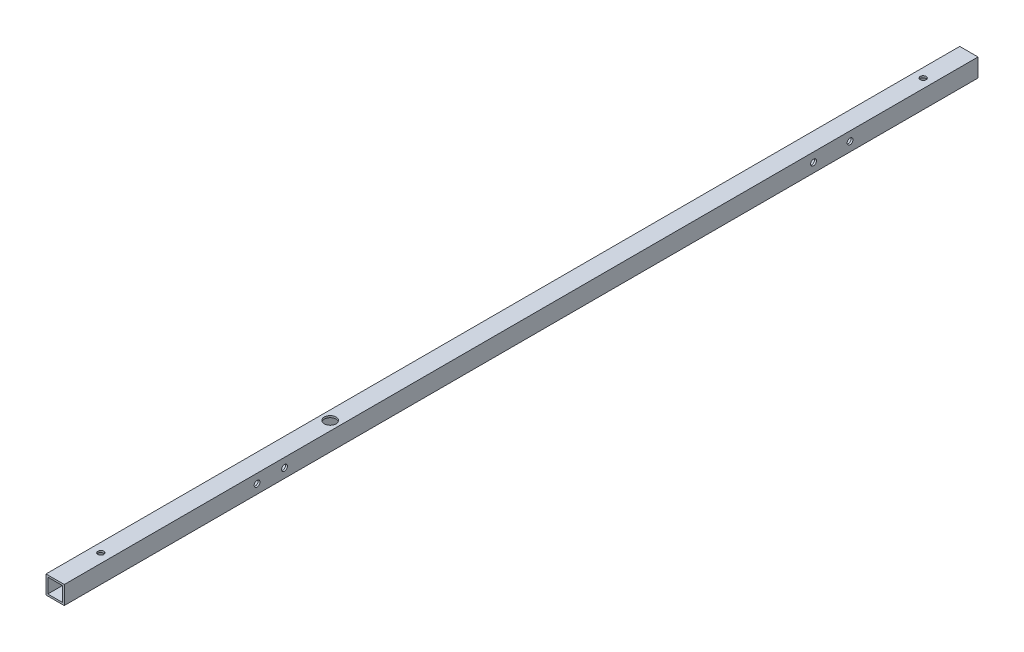
SolidWorks part; units mm, degrees
ref_plane "正面" through (0, 0, 0) normal (0, 0, 1) x (1, 0, 0)
ref_plane "平面" through (0, 0, 0) normal (0, 1, 0) x (1, 0, 0)
ref_plane "右側面" through (0, 0, 0) normal (1, 0, 0) x (0, 0, -1)
sketch "Sketch1" plane through (0, 0, 0) normal (0, 0, 1) x (1, 0, 0)
  line L1 (-5, 5) -> (5, 5)
  line L2 (-5, 5) -> (-5, -5)
  line L3 (-5, -5) -> (5, -5)
  line L4 (5, 5) -> (5, -5)
  line L5 (-5, 5) -> (5, -5) construction
  line L6 (-5, -5) -> (5, 5) construction
  line L7 (-4, 4) -> (4, 4)
  line L8 (-4, 4) -> (-4, -4)
  line L9 (-4, -4) -> (4, -4)
  line L10 (4, 4) -> (4, -4)
  line L11 (-4, 4) -> (4, -4) construction
  line L12 (-4, -4) -> (4, 4) construction
  point P0 (0, 0)
  point P6 (0, 0)
  dimension "D1" = 10
  dimension "D2" = 10
  dimension "D3" = 8
extrude "Boss-Extrude1" add sketch "Sketch1" along normal blind 500
sketch "Sketch2" plane through (0, 5, 0) normal (0, 1, 0) x (1, 0, 0)
  line L0 (-5, -349.5) -> (5, -349.5) construction
  line L1 (-5, -500) -> (-5, 0) construction
  line L2 (5, -500) -> (5, 0) construction
  line L3 (5, -500) -> (-5, -500) construction
  circle A0 centre (0, -349.5) radius 1.6
  dimension "D2" = 3.2
  dimension "D1" = 150.5
extrude "Cut-Extrude1" cut sketch "Sketch2" against normal up to surface (10 mm away) up to face at (0, -5, 250)
sketch "Sketch3" plane through (0, 5, 0) normal (0, 1, 0) x (1, 0, 0)
  line L0 (0, 0) -> (0, -500) construction
  line L1 (5, -500) -> (-5, -500) construction
  line L2 (5, 0) -> (-5, 0) construction
  circle A0 centre (0, -475) radius 1.6
  circle A1 centre (0, -25) radius 1.6
  dimension "D1" = 3.2
  dimension "D3" = 3.2
  dimension "D2" = 25
  dimension "D4" = 25
extrude "Cut-Extrude2" cut sketch "Sketch3" against normal up to surface (10 mm away) up to face at (0, -5, 351.1)
sketch "Sketch4" plane through (5, 0, 0) normal (1, 0, 0) x (0, 0, -1)
  line L0 (-500, 0) -> (0, 0) construction
  line L1 (-500, -5) -> (-500, 5) construction
  line L2 (0, -5) -> (0, 5) construction
  circle A0 centre (-70, 0) radius 1.6
  circle A1 centre (-90, 0) radius 1.6
  circle A2 centre (-394.5, 0) radius 1.6
  circle A3 centre (-379.5, 0) radius 1.6
  dimension "D1" = 3.2
  dimension "D6" = 3.2
  dimension "D2" = 70
  dimension "D3" = 20
  dimension "D4" = 105.5
  dimension "D5" = 15
extrude "Cut-Extrude3" cut sketch "Sketch4" against normal blind 10
sketch "Sketch5" plane through (0, 5, 0) normal (0, 1, 0) x (1, 0, 0)
  circle A0 centre (0, -349.5) radius 3.25
  dimension "D1" = 6.5
extrude "Cut-Extrude4" cut sketch "Sketch5" against normal blind 1
